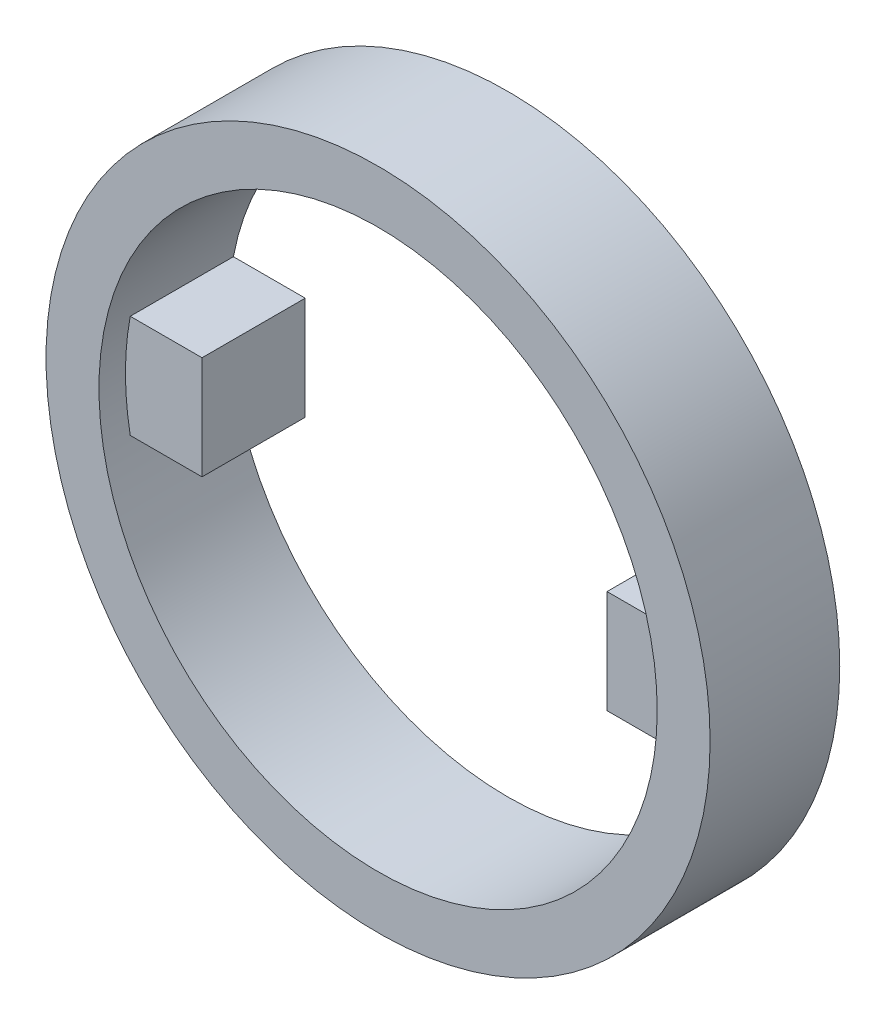
SolidWorks part; units mm, degrees
ref_plane "前视基准面" through (0, 0, 0) normal (0, 0, 1) x (1, 0, 0)
ref_plane "上视基准面" through (0, 0, 0) normal (0, 1, 0) x (1, 0, 0)
ref_plane "右视基准面" through (0, 0, 0) normal (1, 0, 0) x (0, 0, -1)
other "Configuration Table"
sketch "草图1" plane through (0, 0, 0) normal (0, 0, 1) x (1, 0, 0)
  circle A0 centre (0, 0) radius 10.55
  dimension "D1" = 21.1
extrude "拉伸-薄壁1" add sketch "草图1" along normal blind 4.9 thin
sketch "草图2" plane through (0, 0, 0) normal (0, 0, 1) x (1, 0, 0)
  line L0 (-3.2781, 0) -> (3.6158, 0) construction
  line L1 (-11.2099, 1.95) -> (-7.6542, 1.95)
  line L2 (-11.2099, 1.95) -> (-11.2099, -1.95)
  line L3 (-11.2099, -1.95) -> (-7.6542, -1.95)
  line L4 (-7.6542, 1.95) -> (-7.6542, -1.95)
  line L5 (-11.2099, 1.95) -> (-7.6542, -1.95) construction
  line L6 (-11.2099, -1.95) -> (-7.6542, 1.95) construction
  line L7 (0, 3.1867) -> (0, -4.165) construction
  line L8 (11.2099, -1.95) -> (7.6542, -1.95)
  line L9 (7.6542, 1.95) -> (7.6542, -1.95)
  line L10 (11.2099, 1.95) -> (7.6542, 1.95)
  line L11 (11.2099, 1.95) -> (11.2099, -1.95)
  point P0 (-9.432, 0)
  point P11 (0, 0)
  point P12 (0, 0)
  dimension "D1" = 3.9
extrude "凸台-拉伸2" add sketch "草图2" along normal blind 3.9
